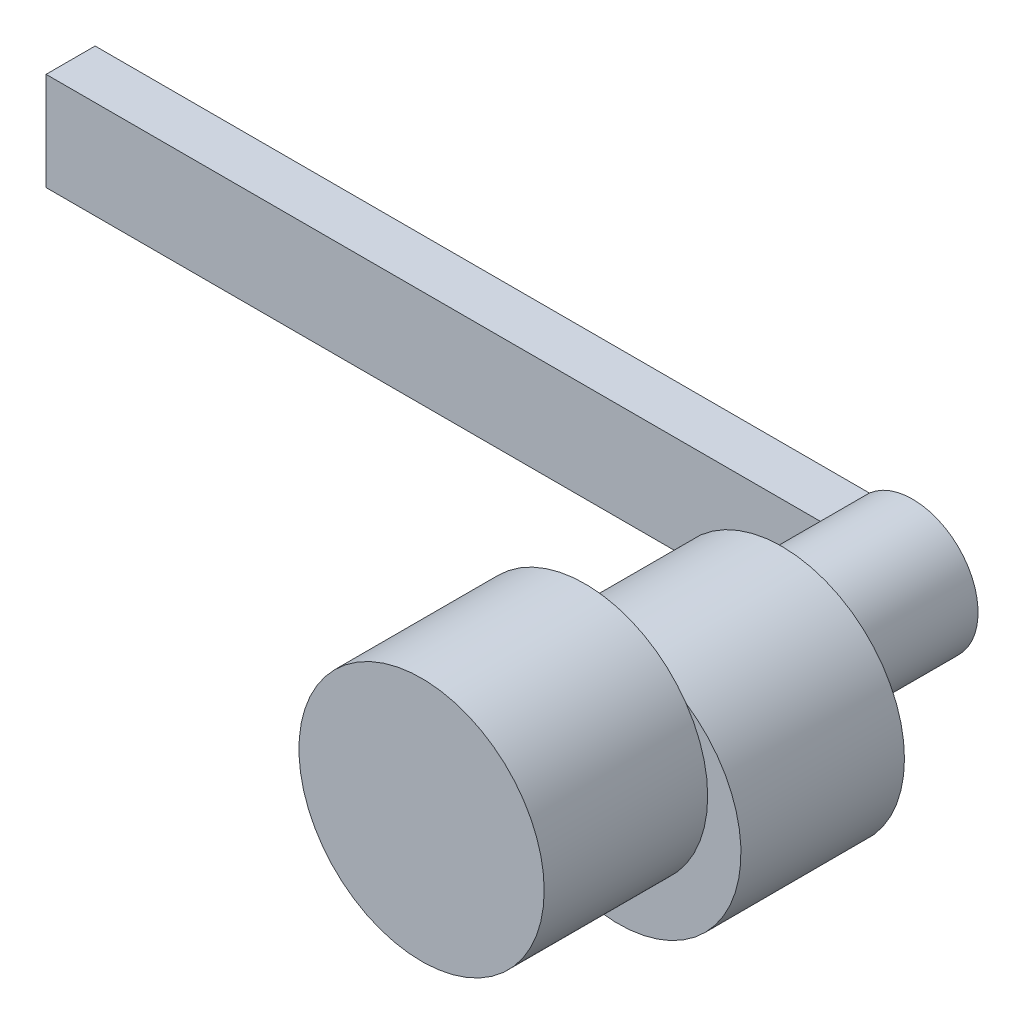
SolidWorks part; units mm, degrees
ref_plane "Front Plane" through (0, 0, 0) normal (0, 0, 1) x (1, 0, 0)
ref_plane "Top Plane" through (0, 0, 0) normal (0, 1, 0) x (1, 0, 0)
ref_plane "Right Plane" through (0, 0, 0) normal (1, 0, 0) x (0, 0, -1)
sketch "Sketch1" plane through (0, 0, 0) normal (0, 0, 1) x (1, 0, 0)
  circle A0 centre (0, 0) radius 4
extrude "Boss-Extrude1" add sketch "Sketch1" along normal blind 10
sketch "Sketch2" plane through (0, 0, 10) normal (0, 0, 1) x (1, 0, 0)
  line L0 (0, 0) -> (2, 0) construction
  circle A0 centre (2, 0) radius 7.5
  dimension "D1" = 15
  dimension "D2" = 2
extrude "Boss-Extrude2" add sketch "Sketch2" along normal blind 10
sketch "Sketch3" plane through (0, 0, 20) normal (0, 0, 1) x (1, 0, 0)
  line L0 (2, 0) -> (-2, 0)
  line L4 (-2, 0) -> (-0.2322, 1.7678)
  line L5 (-0.2322, 1.7678) -> (-0.2322, -1.7678)
  line L6 (-0.2322, -1.7678) -> (-2, 0)
  line L7 (2, 0.5) -> (-2, 0.5)
  line L8 (2, -0.5) -> (-2, -0.5)
  line L9 (2, -0.5) -> (2, 0.5)
  dimension "D1" = 0.5
  dimension "D2" = 0.5
extrude "Cut-Extrude1" cut sketch "Sketch3" against normal blind 0.1 contours L7 L5 L4 | L5 L7 L4 L0 | L8 L5 L0 L6 | L5 L8 L6 | L0 L9 L7 L5 | L8 L9 L0 L5
sketch "Sketch6" plane through (0, 0, 20) normal (0, 0, 1) x (1, 0, 0)
  line L0 (0, 0) -> (-0.0349, 1.9997) construction
  line L1 (0, 0) -> (0, 4.0204) construction
  circle A0 centre (-0.0349, 1.9997) radius 7.5
  dimension "D2" = 15
  dimension "D1" = 1
  dimension "D3" = 2
extrude "Boss-Extrude5" add sketch "Sketch6" along normal blind 10
sketch "Sketch7" plane through (0, 0, 0) normal (0, 0, -1) x (-1, 0, 0)
  line L0 (0, 0) -> (50, 0) construction
  line L1 (0, -3) -> (50, -3)
  line L2 (0, 3) -> (50, 3)
  line L3 (0, 3) -> (0, -3)
  line L4 (50, 3) -> (50, -3)
  dimension "D1" = 3
  dimension "D2" = 3
extrude "Boss-Extrude6" add sketch "Sketch7" against normal blind 3
